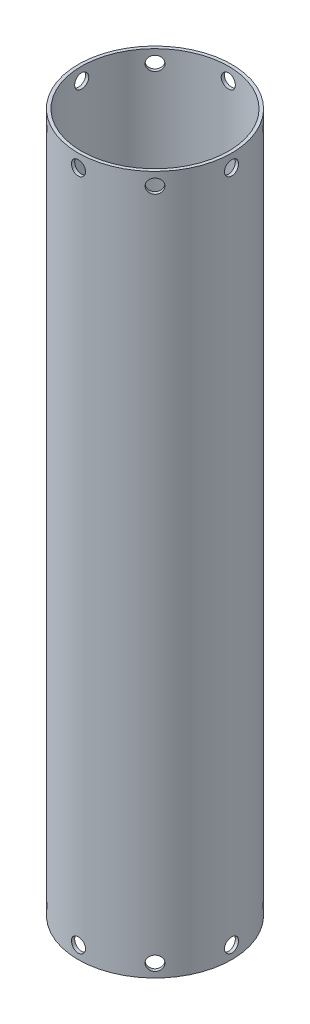
SolidWorks part; units mm, degrees
material "6061-T6 (SS)"
ref_plane "Front Plane" through (0, 0, 0) normal (0, 0, 1) x (1, 0, 0)
ref_plane "Top Plane" through (0, 0, 0) normal (0, 1, 0) x (1, 0, 0)
ref_plane "Right Plane" through (0, 0, 0) normal (1, 0, 0) x (0, 0, -1)
sketch "Sketch1" plane through (0, 0, 0) normal (0, 1, 0) x (1, 0, 0)
  circle A0 centre (0, 0) radius 76.2
  circle A1 centre (0, 0) radius 73.025
  dimension "D1" = 152.4
  dimension "D2" = 3.175
extrude "Boss-Extrude1" add sketch "Sketch1" along normal blind 693.1406
sketch "Sketch2" plane through (0, 667.7406, 0) normal (1, 0, 0) x (0, 0, 1)
  circle A0 centre (0, -12.7) radius 5.715 construction
  circle A1 centre (0, -12.7) radius 5.715 construction
  circle A2 centre (0, -12.7) radius 6.985
  dimension "D1" = 1.27
extrude "LOX Top Holes" cut sketch "Sketch2" along normal up to surface (75.8792 mm away) contours A2
pattern_circular "CirPattern1" count 8 over 360 about axis through (0, 693.1406, 0) along (0, 1, 0) of "LOX Top Holes"
sketch "Sketch3" plane through (0, 25.4, 0) normal (1, 0, 0) x (0, 0, -1)
  circle A0 centre (0, -12.7) radius 5.715 construction
  circle A1 centre (0, -12.7) radius 5.715 construction
  circle A2 centre (0, -12.7) radius 6.985
  dimension "D1" = 1.27
extrude "LOX Bottom Holes" cut sketch "Sketch3" along normal up to surface (75.8792 mm away) contours A2
pattern_circular "CirPattern2" count 8 over 360 about axis through (0, 0, 0) along (0, 1, 0) of "LOX Bottom Holes"
sketch "Sketch4" [suppressed] plane through (0, 431.8, 0) normal (1, 0, 0) x (0, 0, 1)
  circle A0 centre (0, -12.7) radius 5.715 construction
  circle A1 centre (0, -12.7) radius 5.715 construction
  circle A2 centre (0, -12.7) radius 6.985
  dimension "D1" = 1.27
extrude "Cut-Extrude1" [suppressed] cut sketch "Sketch4" along normal up to surface (75.8792 mm away) contours A2
pattern_circular "CirPattern3" [suppressed] count 8 over 360
sketch "Sketch7" [suppressed] plane through (0, 25.4, 0) normal (1, 0, 0) x (0, 0, -1)
  circle A0 centre (0, -12.7) radius 5.715 construction
  circle A1 centre (0, -12.7) radius 5.715 construction
  circle A2 centre (0, -12.7) radius 6.985
  dimension "D1" = 1.27
extrude "Cut-Extrude2" [suppressed] cut sketch "Sketch7" along normal up to surface (75.8792 mm away)
pattern_circular "CirPattern4" [suppressed] count 8 over 360
